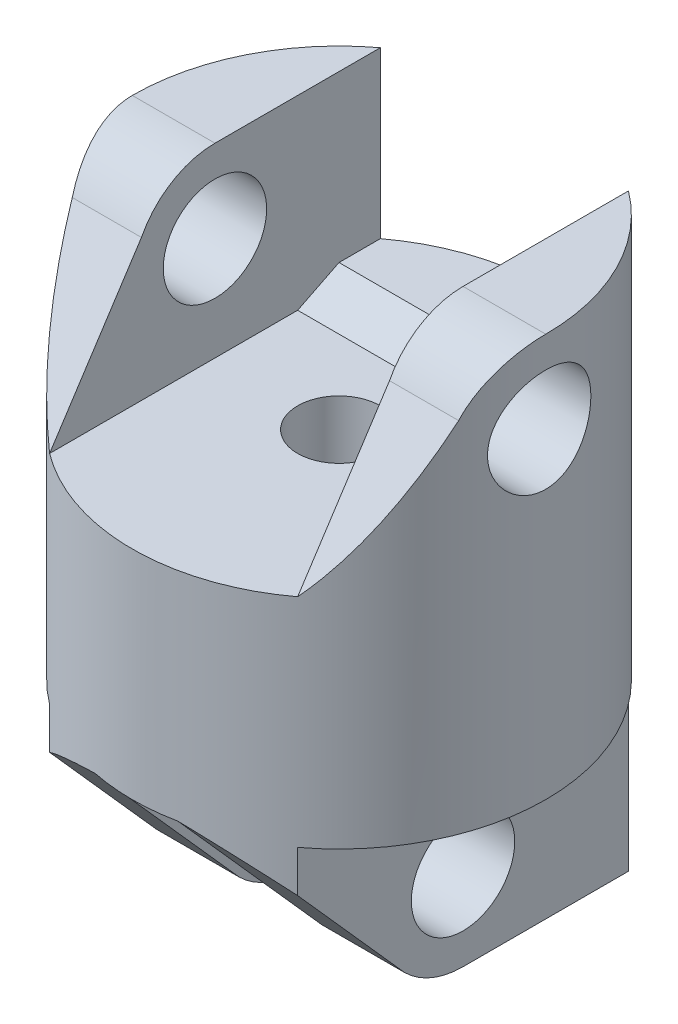
SolidWorks part; units mm, degrees
ref_plane "Front Plane" through (0, 0, 0) normal (0, 0, 1) x (1, 0, 0)
ref_plane "Top Plane" through (0, 0, 0) normal (0, 1, 0) x (1, 0, 0)
ref_plane "Right Plane" through (0, 0, 0) normal (1, 0, 0) x (0, 0, -1)
sketch "Sketch1" plane through (0, 0, 0) normal (0, 1, 0) x (1, 0, 0)
  circle A0 centre (0, 0) radius 12.7
  dimension "D1" = 25.4
extrude "Boss-Extrude1" add sketch "Sketch1" along normal blind 36.195
sketch "Sketch2" plane through (0, 36.195, 0) normal (0, 1, 0) x (1, 0, 0)
  line L0 (7.62, 10.16) -> (7.62, -10.16)
  line L1 (-7.62, 10.16) -> (-7.62, -10.16)
  arc A0 (-7.62, -10.16) -> (7.62, -10.16) centre (0, 0) ccw
  arc A1 (7.62, 10.16) -> (-7.62, 10.16) centre (0, 0) ccw
  dimension "D2" = 25.4
  dimension "D1" = 7.62
  dimension "D3" = 7.62
extrude "Cut-Extrude1" cut sketch "Sketch2" against normal blind 11.43
sketch "Sketch3" plane through (0, 0, 0) normal (0, -1, 0) x (1, 0, 0)
  line L0 (-2.54, 12.4434) -> (-2.54, -12.4434)
  line L1 (-7.62, 10.16) -> (-7.62, -10.16)
  line L2 (2.54, 12.4434) -> (2.54, -12.4434)
  line L3 (7.62, 10.16) -> (7.62, -10.16)
  arc A0 (-7.62, 10.16) -> (-7.62, -10.16) centre (0, 0) ccw
  arc A1 (-2.54, -12.4434) -> (2.54, -12.4434) centre (0, 0) ccw
  arc A2 (7.62, -10.16) -> (7.62, 10.16) centre (0, 0) ccw
  arc A3 (2.54, 12.4434) -> (-2.54, 12.4434) centre (0, 0) ccw
  dimension "D1" = 25.4
  dimension "D2" = 2.54
  dimension "D3" = 5.08
  dimension "D4" = 2.54
  dimension "D5" = 5.08
extrude "Cut-Extrude2" cut sketch "Sketch3" against normal blind 11.43
sketch "Sketch4" plane through (-7.62, 0, 0) normal (1, 0, 0) x (0, 0, -1)
  line L0 (10.16, 36.195) -> (-10.16, 36.195) construction
  line L5 (10.16, 0) -> (-10.16, 0) construction
  line L6 (10.16, 36.195) -> (-10.16, 36.195) construction
  line L7 (-10.16, 24.765) -> (-4.5178, 33.4378)
  line L9 (-10.16, 24.765) -> (-10.16, 36.195)
  line L10 (-10.16, 36.195) -> (0, 36.195)
  line L11 (0, 0) -> (-12.4434, 0)
  line L12 (-12.4434, 0) -> (-12.4434, 11.43)
  line L13 (-12.4434, 11.43) -> (-3.5921, 1.4879)
  circle A0 centre (0, 31.115) radius 3.175
  circle A2 centre (0, 5.08) radius 3.175
  arc A3 (0, 36.195) -> (-4.5178, 33.4378) centre (0, 31.115) ccw
  arc A4 (0, 0) -> (-3.5921, 1.4879) centre (0, 5.08) cw
  dimension "D1" = 6.35
  dimension "D3" = 6.35
  dimension "D2" = 5.08
  dimension "D4" = 5.08
  dimension "D5" = 0
extrude "Cut-Extrude3" cut sketch "Sketch4" against normal through all both and the other way through all
sketch "Sketch5" plane through (0, 24.765, 0) normal (0, 1, 0) x (1, 0, 0)
  circle A0 centre (0, 0) radius 2.54
  dimension "D1" = 5.08
extrude "Cut-Extrude4" cut sketch "Sketch5" against normal through all
sketch "Sketch6" plane through (-7.62, 0, 0) normal (1, 0, 0) x (0, 0, -1)
  line L6 (5.08, 24.765) -> (10.16, 24.765)
  line L7 (10.16, 24.765) -> (-10.16, 24.765) construction
  line L8 (10.16, 24.765) -> (10.16, 26.035)
  line L9 (10.16, 24.765) -> (10.16, 36.195) construction
  line L10 (10.16, 26.035) -> (7.62, 26.035)
  line L11 (7.62, 26.035) -> (5.08, 24.765)
  point P9 (0, 24.765)
  dimension "D1" = 5.08
  dimension "D2" = 2.54
  dimension "D3" = 1.27
extrude "Boss-Extrude2" add sketch "Sketch6" along normal up to surface (15.24 mm away) up to face at (7.62, 31.115, -3.175)
sketch "Sketch7" plane through (0, 24.765, 0) normal (0, 1, 0) x (1, 0, 0)
  line L0 (-7.62, 10.16) -> (7.62, 10.16)
  arc A0 (-7.62, 10.16) -> (7.62, 10.16) centre (0, 0) cw
  arc A1 (12.7, 0) -> (7.62, 10.16) centre (0, 0) ccw construction
  arc M1 (7.62, 10.16) -> (-7.62, 10.16) centre (0, 0) ccw
  line M2 (-7.62, 10.16) -> (7.62, 10.16)
extrude "Boss-Extrude3" add sketch "Sketch7" along normal up to surface (1.27 mm away) contours M2 M1 up to face at (0, 26.035, -8.89)
equation "\"0..50in\"=0.4"
